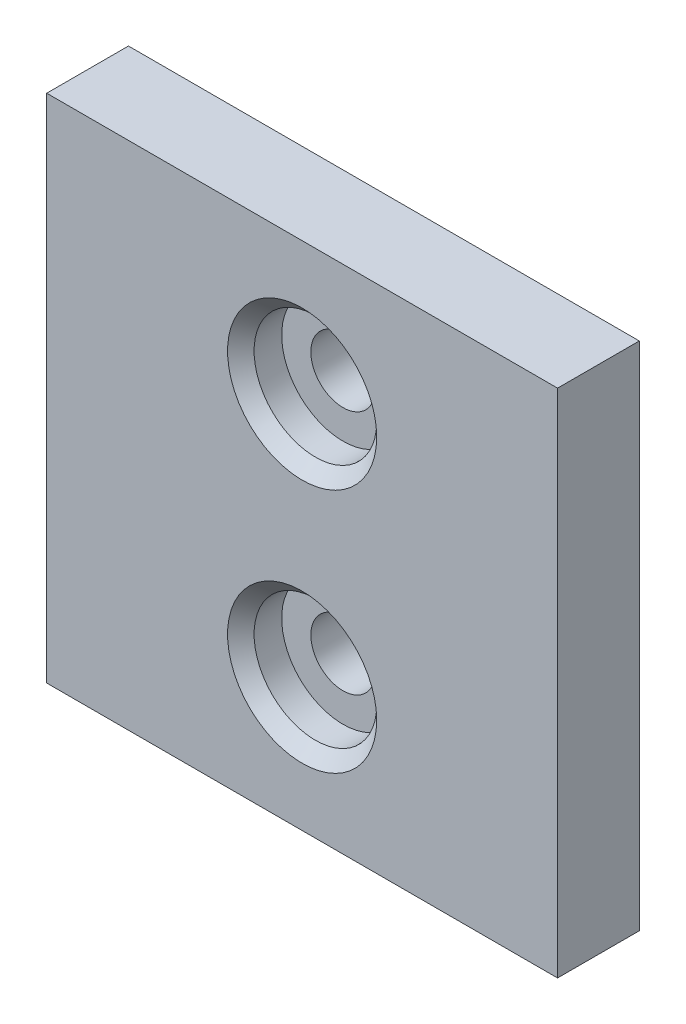
SolidWorks part; units mm, degrees
ref_plane "Front Plane" through (0, 0, 0) normal (0, 0, 1) x (1, 0, 0)
ref_plane "Top Plane" through (0, 0, 0) normal (0, 1, 0) x (1, 0, 0)
ref_plane "Right Plane" through (0, 0, 0) normal (1, 0, 0) x (0, 0, -1)
sketch "Sketch1" plane through (0, 0, 0) normal (0, 0, 1) x (1, 0, 0)
  line L1 (-25, 25) -> (25, 25)
  line L2 (-25, 25) -> (-25, -25)
  line L3 (-25, -25) -> (25, -25)
  line L4 (25, 25) -> (25, -25)
  line L5 (-25, 25) -> (25, -25) construction
  line L6 (-25, -25) -> (25, 25) construction
  point P0 (0, 0)
  dimension "D1" = 50
  dimension "D2" = 50
extrude "Boss-Extrude1" add sketch "Sketch1" along normal blind 8
sketch "Sketch2" plane through (0, 0, 8) normal (0, 0, 1) x (1, 0, 0)
  line L0 (0, -1000) -> (0, 49000) construction
  line L1 (-1000, 0) -> (49000, 0) construction
  point P1 (0, -12)
  point P4 (0, 12)
  point P5 (0, 0)
  dimension "D1" = 24
hole_wizard "CBORE for M6 Hex Head Bolt2" positions "Sketch13" profile "Sketch14" counterbore size "M6" standard "ISO" end condition through all
sketch "Sketch13" plane through (0, 0, 8) normal (0, 0, 1) x (1, 0, 0)
  point P0 (0, -12)
  point P2 (0, 12)
  point P6 (0, -12)
  point P10 (0, 0)
  point P12 (0, 0)
sketch "Sketch14" plane through (0, -12, 8) normal (1, 0, 0) x (0, -1, 0)
  line L0 (0, 0) -> (0, 8)
  line L1 (0, 8) -> (3.15, 8)
  line L3 (3.15, 8) -> (3.15, 4)
  line L4 (6, 4) -> (3.15, 4)
  line L5 (6, 4) -> (6, 1.2985)
  line L6 (6, 1.2985) -> (7.2985, 0)
  line L7 (7.2985, 0) -> (0, 0)
  line L8 (-6, 1.2985) -> (-7.2985, 0) construction
  line L11 (0, -6.35) -> (0, 107.95) construction
  dimension "Thru Hole Dia." = 6.3
  dimension "Thru Hole Depth" = 8
  dimension "C'Bore Dia." = 12
  dimension "C'Bore Depth" = 4
  dimension "Near C'Sink Dia." = 14.597
  dimension "Near C'Sink Angle" = 90
